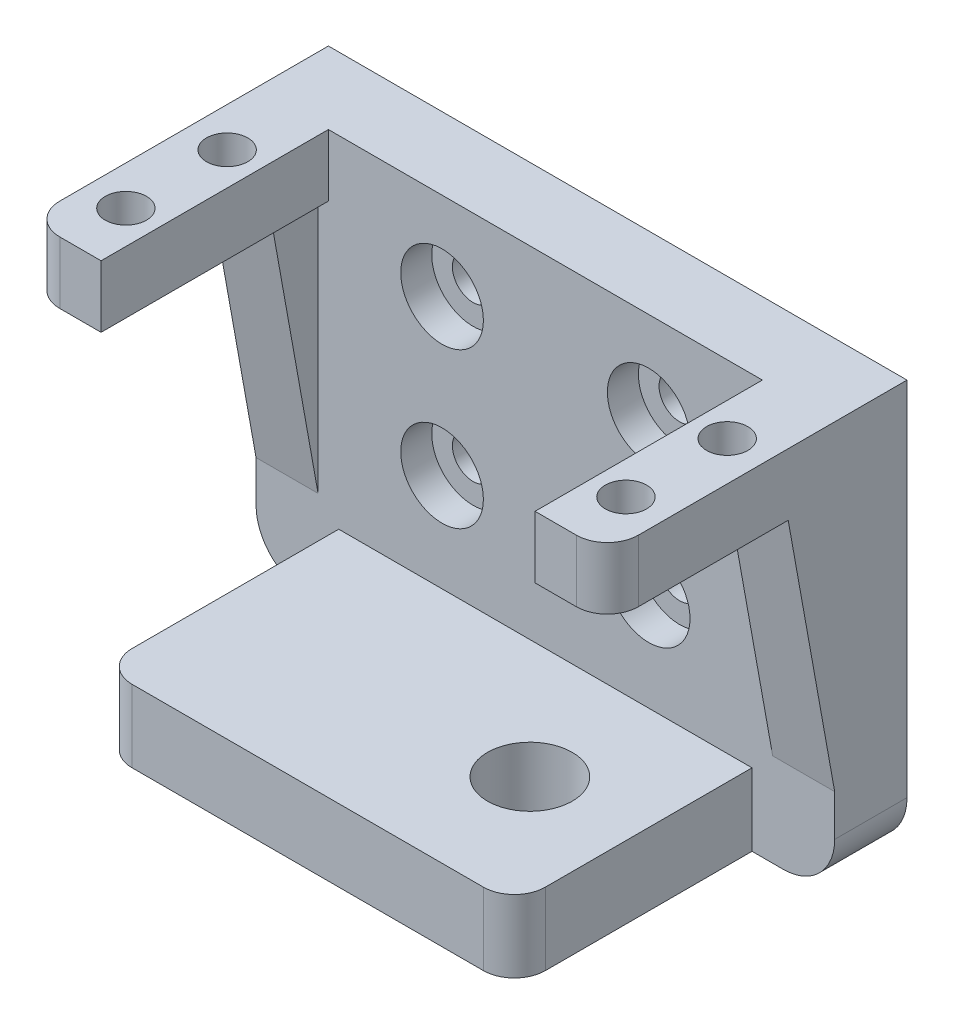
SolidWorks part; units mm, degrees
ref_plane "前视基准面" through (0, 0, 0) normal (0, 0, 1) x (1, 0, 0)
ref_plane "上视基准面" through (0, 0, 0) normal (0, 1, 0) x (1, 0, 0)
ref_plane "右视基准面" through (0, 0, 0) normal (1, 0, 0) x (0, 0, -1)
sketch "草图4" plane through (0, 0, 0) normal (0, 1, 0) x (1, 0, 0)
  line L0 (0, 17.6534) -> (0, -5.833) construction
  line L1 (-24.2, 14.9) -> (-24.2, 5.1) construction
  line L2 (-28, 28.5) -> (28, 28.5)
  line L3 (-28, 28.5) -> (-28, 2.5)
  line L4 (-25, -0.5) -> (-21, -0.5)
  line L5 (28, 28.5) -> (28, 2.5)
  line L6 (-28, 28.5) -> (28, -0.5) construction
  line L7 (-28, -0.5) -> (28, 28.5) construction
  line L8 (-21, 21.5) -> (21, 21.5)
  line L9 (-21, 21.5) -> (-21, -0.5)
  line L11 (21, 21.5) -> (21, -0.5)
  line L12 (-21, 21.5) -> (21, -0.5) construction
  line L13 (-21, -0.5) -> (21, 21.5) construction
  line L14 (21, -0.5) -> (25, -0.5)
  line L16 (24.2, 14.9) -> (24.2, 5.1) construction
  circle A0 centre (-24.2, 14.9) radius 2
  circle A1 centre (-24.2, 5.1) radius 2
  circle A2 centre (24.2, 14.9) radius 2
  circle A3 centre (24.2, 5.1) radius 2
  arc A4 (25, -0.5) -> (28, 2.5) centre (25, 2.5) ccw
  arc A5 (-25, -0.5) -> (-28, 2.5) centre (-25, 2.5) cw
  point P3 (0, 14)
  point P8 (0, 10.5)
  dimension "D6" = 4
  dimension "D7" = 4
  dimension "D8" = 4
  dimension "D9" = 4
  dimension "D10" = 3
  dimension "D1" = 22
  dimension "D3" = 7
  dimension "D4" = 42
  dimension "D5" = 7
  dimension "D11" = 24.2
  dimension "D12" = 9.8
  dimension "D13" = 24.2
  dimension "D14" = 9.8
extrude "凸台-拉伸1" add sketch "草图4" against normal blind 6 from surface
sketch "草图5" plane through (0, 0, -28.5) normal (0, 0, -1) x (-1, 0, 0)
  line L0 (0, 4.5795) -> (0, 37.3232) construction
  line L1 (-28, 74.5) -> (28, 74.5) construction
  line L2 (-20, 74.5) -> (20, 74.5)
  line L3 (-20, 74.5) -> (-20, 40.5)
  line L4 (-20, 40.5) -> (20, 40.5)
  line L5 (20, 74.5) -> (20, 40.5)
  line L6 (-20, 74.5) -> (20, 40.5) construction
  line L7 (-20, 40.5) -> (20, 74.5) construction
  line L8 (-20, 64.5) -> (20, 64.5) construction
  circle A0 centre (-10, 72) radius 2
  circle A1 centre (10, 72) radius 2
  circle A4 centre (10, 57) radius 2
  circle A5 centre (-10, 57) radius 2
  point P3 (0, 57.5)
  dimension "D3" = 4
  dimension "D1" = 40
  dimension "D2" = 34
  dimension "D4" = 20
  dimension "D6" = 10
  dimension "D7" = 15
extrude "凸台-拉伸2" add sketch "草图5" against normal blind 7
sketch "草图6" plane through (0, 0, 0) normal (0, 0, 1) x (1, 0, 0)
  circle A0 centre (-10, 72) radius 4
  circle A1 centre (10, 72) radius 4
  circle A5 centre (-10, 57) radius 4
  circle A6 centre (10, 57) radius 4
  dimension "D1" = 8
extrude "切除-拉伸1" cut sketch "草图6" against normal blind 3 from surface at -21.5 starting at face at (0, 67.5, -21.5)
sketch "草图7" plane through (0, 0, 0) normal (0, 1, 0) x (1, 0, 0)
  line L0 (-20, 21.5) -> (-20, 28.5) construction
  line L1 (20, 21.5) -> (-20, 21.5)
  line L2 (20, 21.5) -> (20, 1.5)
  line L3 (17, -1.5) -> (-17, -1.5)
  line L4 (-20, 21.5) -> (-20, 1.5)
  circle A0 centre (10, 10) radius 4.1
  arc A1 (-17, -1.5) -> (-20, 1.5) centre (-17, 1.5) cw
  arc A2 (17, -1.5) -> (20, 1.5) centre (17, 1.5) ccw
  point P14 (20, -1.5)
  dimension "D1" = 8.2
  dimension "D3" = 3
  dimension "D2" = 23
  dimension "D4" = 11.5
  dimension "D5" = 10
extrude "凸台-拉伸3" add sketch "草图7" along normal blind 7 from surface at 40.5 starting at face at (0, 40.5, -25)
sketch "草图8" plane through (0, 40.5, 0) normal (0, -1, 0) x (1, 0, 0)
  circle A0 centre (10, -10) radius 4.9
  dimension "D1" = 9.8
extrude "切除-拉伸2" cut sketch "草图8" against normal blind 0.9
sketch "草图10" plane through (20, 0, 0) normal (1, 0, 0) x (0, 0, -1)
  line L0 (28.5, 49.5) -> (28.5, 74.5)
  line L1 (28.5, 74.5) -> (28.5, 40.5) construction
  line L2 (28.5, 74.5) -> (17, 74.5)
  line L3 (2.5, 74.5) -> (28.5, 74.5) construction
  line L4 (17, 74.5) -> (21.5, 49.5)
  line L5 (21.5, 74.5) -> (21.5, 47.5) construction
  line L6 (21.5, 49.5) -> (28.5, 49.5)
  dimension "D1" = 25
  dimension "D2" = 11.5
extrude "凸台-拉伸4" add sketch "草图10" along normal blind 6 from offset 2
sketch "草图12" plane through (-20, 0, 0) normal (-1, 0, 0) x (0, 0, 1)
  line L2 (-17, 74.5) -> (-21.5, 49.5) construction
  line L3 (-21.5, 47.5) -> (-21.5, 74.5) construction
  line L4 (-21.5, 49.5) -> (-28.5, 49.5)
  line L5 (-28.5, 40.5) -> (-28.5, 74.5) construction
  line L6 (-28.5, 49.5) -> (-28.5, 74.5)
  line L7 (-21.5, 49.5) -> (-17, 74.5)
  line L8 (-17, 74.5) -> (-28.5, 74.5)
extrude "凸台-拉伸5" add sketch "草图12" along normal blind 6 from offset 2
sketch "草图13" plane through (0, 0, -28.5) normal (0, 0, -1) x (-1, 0, 0)
  line L0 (-20, 40.5) -> (20, 40.5) construction
  line L1 (28, 80.5) -> (-28, 80.5)
  line L2 (28, 80.5) -> (28, 45.5)
  line L3 (23, 40.5) -> (-23, 40.5)
  line L4 (-28, 80.5) -> (-28, 45.5)
  line L5 (-28, 49.5) -> (-28, 80.5) construction
  line L6 (0, 0) -> (0, 19.1257) construction
  line L7 (-15, 77.5) -> (15, 77.5)
  line L8 (-15, 77.5) -> (-15, 52.5)
  line L9 (-15, 52.5) -> (15, 52.5)
  line L10 (15, 77.5) -> (15, 52.5)
  line L11 (-15, 77.5) -> (15, 52.5) construction
  line L12 (-15, 52.5) -> (15, 77.5) construction
  arc A0 (-28, 45.5) -> (-23, 40.5) centre (-23, 45.5) ccw
  arc A1 (28, 45.5) -> (23, 40.5) centre (23, 45.5) cw
  point P13 (0, 65)
  dimension "D1" = 5
  dimension "D2" = 30
  dimension "D3" = 25
  dimension "D4" = 3
extrude "凸台-拉伸6" add sketch "草图13" against normal blind 7
